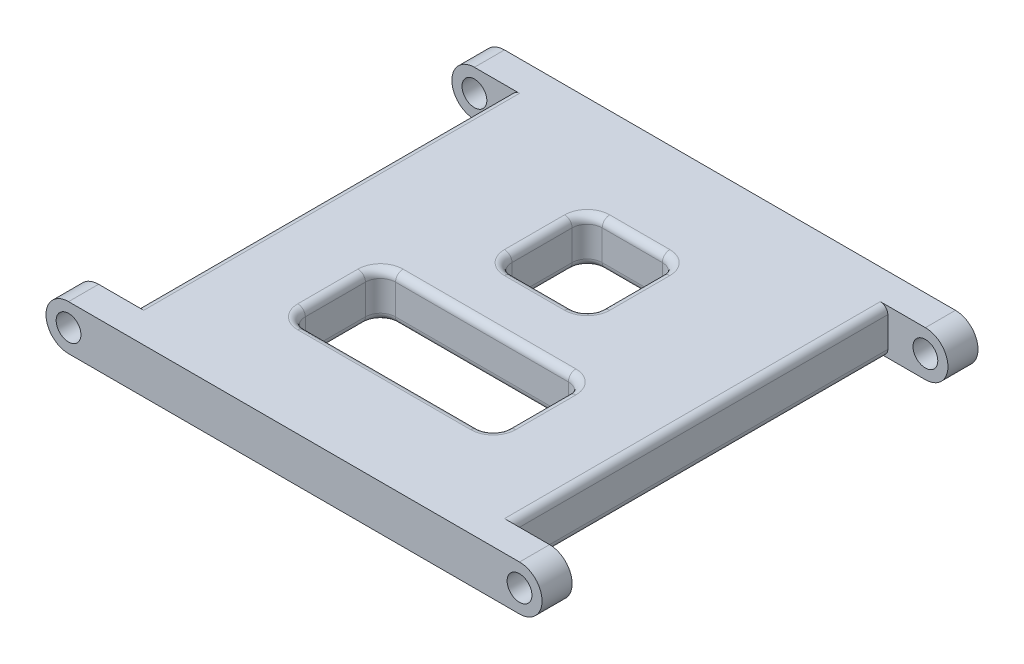
SolidWorks part; units mm, degrees
ref_plane "Front Plane" through (0, 0, 0) normal (0, 0, 1) x (1, 0, 0)
ref_plane "Top Plane" through (0, 0, 0) normal (0, 1, 0) x (1, 0, 0)
ref_plane "Right Plane" through (0, 0, 0) normal (1, 0, 0) x (0, 0, -1)
sketch "Sketch1" plane through (0, 0, 0) normal (0, 0, 1) x (1, 0, 0)
  line L0 (0, 0) -> (60, 0)
  line L1 (0, 3) -> (60, 3)
  line L2 (60, -3) -> (0, -3)
  circle A0 centre (0, 0) radius 1.65
  circle A1 centre (60, 0) radius 1.65
  circle A2 centre (0, 0) radius 3
  circle A3 centre (60, 0) radius 3
  dimension "D2" = 3.3
  dimension "D3" = 6
  dimension "D4" = 6
  dimension "D1" = 60
extrude "Boss-Extrude1" add sketch "Sketch1" along normal blind 4
sketch "Sketch2" plane through (0, 0, 4) normal (0, 0, 1) x (1, 0, 0)
  line L0 (0, 3) -> (60, -3)
  line L2 (0, 3) -> (60, 3)
  line L3 (0, 3) -> (0, -3)
  line L4 (0, -3) -> (60, -3)
  line L5 (60, 3) -> (60, -3)
  line L6 (55, 3) -> (5, 3)
  line L7 (55, 3) -> (55, -3)
  line L8 (55, -3) -> (5, -3)
  line L9 (5, 3) -> (5, -3)
  line L10 (55, 3) -> (5, -3) construction
  line L11 (55, -3) -> (5, 3) construction
  point P4 (30, 0)
  dimension "D1" = 50
extrude "Boss-Extrude2" add sketch "Sketch2" along normal blind 25 contours L0 L9 L4 L7 | L2 L9 L0 L7
mirror "Mirror1" about plane through (0, 0, 29) normal (0, 0, 1) of bodies 102
sketch "Sketch4" plane through (0, -3, 0) normal (0, -1, 0) x (1, 0, 0)
  line L0 (5, 54) -> (55, 4)
  line L1 (5, 54) -> (55, 54)
  line L2 (5, 54) -> (5, 4)
  line L3 (5, 4) -> (55, 4)
  line L4 (55, 54) -> (55, 4)
  line L5 (16.5, 43) -> (16.5, 35)
  line L6 (16.5, 35) -> (43.5, 35) construction
  line L7 (16.5, 35) -> (16.5, 23) construction
  line L8 (16.5, 23) -> (43.5, 23) construction
  line L9 (43.5, 35) -> (43.5, 23) construction
  line L10 (16.5, 35) -> (43.5, 23) construction
  line L11 (16.5, 23) -> (43.5, 35) construction
  line L12 (18.5, 45) -> (41.5, 45)
  line L13 (43.5, 43) -> (43.5, 35)
  line L14 (18.5, 33) -> (41.5, 33)
  line L15 (24, 23) -> (24, 15)
  line L16 (24, 35) -> (36, 35) construction
  line L17 (24, 35) -> (24, 23) construction
  line L18 (24, 23) -> (36, 23) construction
  line L19 (36, 35) -> (36, 23) construction
  line L20 (24, 35) -> (36, 23) construction
  line L21 (24, 23) -> (36, 35) construction
  line L22 (26, 25) -> (34, 25)
  line L23 (36, 23) -> (36, 15)
  line L24 (26, 13) -> (34, 13)
  arc A1 (34, 13) -> (36, 15) centre (34, 15) ccw
  arc A2 (36, 23) -> (34, 25) centre (34, 23) ccw
  arc A3 (26, 25) -> (24, 23) centre (26, 23) ccw
  arc A4 (26, 13) -> (24, 15) centre (26, 15) cw
  arc A5 (43.5, 43) -> (41.5, 45) centre (41.5, 43) ccw
  arc A6 (43.5, 35) -> (41.5, 33) centre (41.5, 35) cw
  arc A7 (18.5, 33) -> (16.5, 35) centre (18.5, 35) cw
  arc A8 (18.5, 45) -> (16.5, 43) centre (18.5, 43) ccw
  point P6 (30, 29)
  point P11 (30, 29)
  dimension "D4" = 12
  dimension "D7" = 2
  dimension "D1" = 27
  dimension "D2" = 12
  dimension "D5" = 12
  dimension "D3" = 2
  dimension "D6" = 2
extrude "Cut-Extrude1" cut sketch "Sketch4" against normal blind 25 contours L12 A8 L5 L0 L14 A6 L13 A5 | A7 L14 L0 L5 | A4 L24 A1 L23 L0 L22 A3 L15 | L0 A2
fillet "Fillet1" radius 1 36 edges at (55, 3, 29) (55, -3, 29) (5, -3, 29) (5, 3, 29) (24.5858, -3, 24.4142) (30, -3, 25) (35.4142, -3, 24.4142) (36, -3, 19) (35.4142, -3, 13.5858) (30, -3, 13) (24.5858, -3, 13.5858) (24.5858, 3, 13.5858) (30, 3, 13) (35.4142, 3, 13.5858) (36, 3, 19) (35.4142, 3, 24.4142) (30, 3, 25) (24.5858, 3, 24.4142) (17.0858, -3, 44.4142) (30, -3, 45) (42.9142, -3, 44.4142) (43.5, -3, 39) (42.9142, -3, 33.5858) (30, -3, 33) (17.0858, -3, 33.5858) (17.0858, 3, 33.5858) (30, 3, 33) (42.9142, 3, 33.5858) (43.5, 3, 39) (42.9142, 3, 44.4142) (30, 3, 45) (17.0858, 3, 44.4142) (24, -3, 19) (24, 3, 19) (16.5, -3, 39) (16.5, 3, 39)
